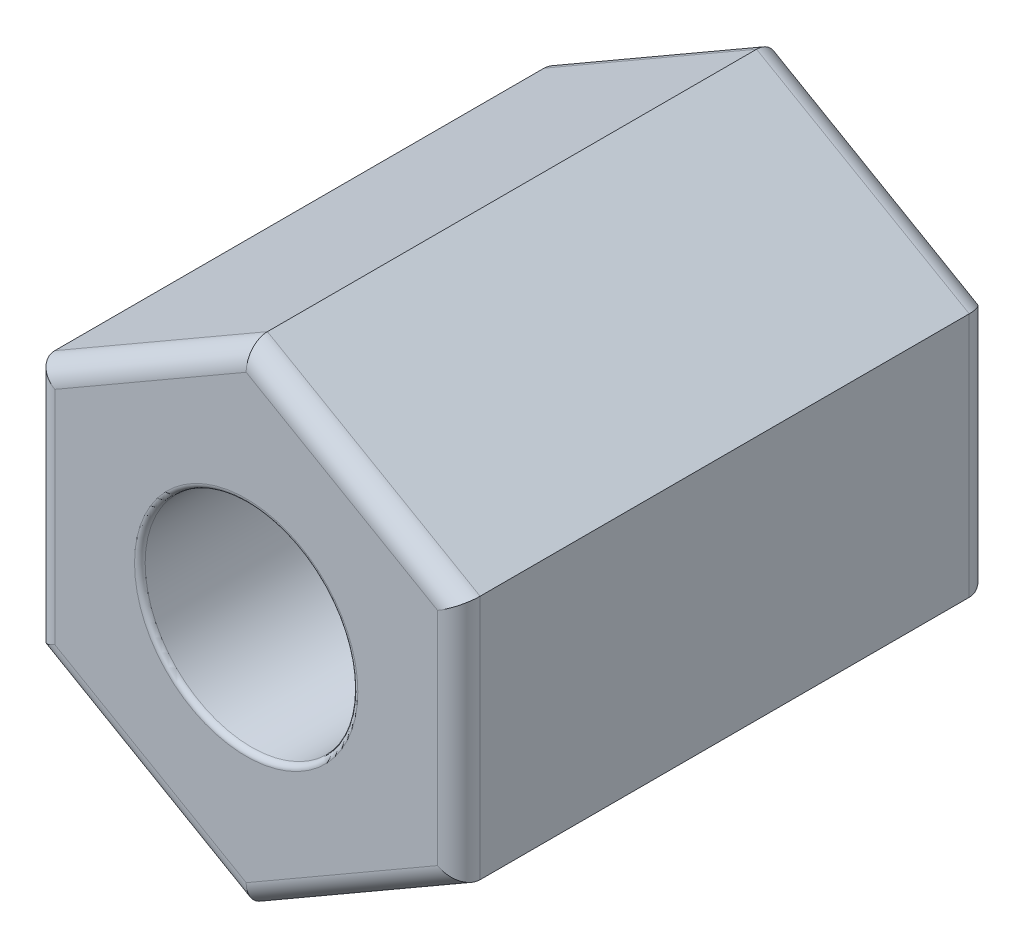
SolidWorks part; units mm, degrees
ref_plane "前视基准面" through (0, 0, 0) normal (0, 0, 1) x (1, 0, 0)
ref_plane "上视基准面" through (0, 0, 0) normal (0, 1, 0) x (1, 0, 0)
ref_plane "右视基准面" through (0, 0, 0) normal (1, 0, 0) x (0, 0, -1)
sketch "草图1" plane through (0, 0, 0) normal (0, 0, 1) x (1, 0, 0)
  line L1 (0, -23.094) -> (20, -11.547)
  line L2 (20, -11.547) -> (20, 11.547)
  line L3 (20, 11.547) -> (0, 23.094)
  line L4 (0, 23.094) -> (-20, 11.547)
  line L5 (-20, 11.547) -> (-20, -11.547)
  line L6 (-20, -11.547) -> (0, -23.094)
  circle A0 centre (0, 0) radius 20 construction
  circle A1 centre (0, 0) radius 10
  dimension "D1" = 20
  dimension "D2" = 40
extrude "凸台-拉伸1" add sketch "草图1" along normal blind 50
fillet "圆角1" radius 2 12 edges at (10, -17.3205, 0) (-10, -17.3205, 0) (-20, 0, 0) (-10, 17.3205, 0) (10, 17.3205, 0) (20, 0, 0) (20, 0, 50) (10, -17.3205, 50) (-10, -17.3205, 50) (-20, 0, 50) (-10, 17.3205, 50) (10, 17.3205, 50)
fillet "圆角2" radius 0.5 2 edges at (10, 0, 0) (10, 0, 50)
